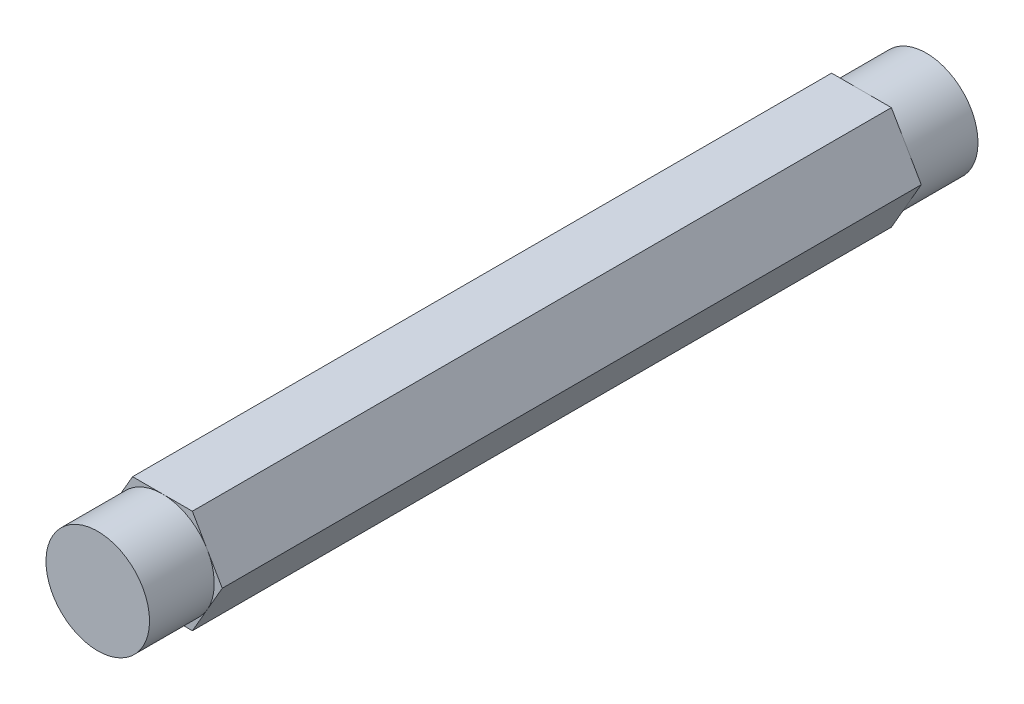
SolidWorks part; units mm, degrees
material "6061-T6 (SS)"
ref_plane "Front Plane" through (0, 0, 0) normal (0, 0, 1) x (1, 0, 0)
ref_plane "Top Plane" through (0, 0, 0) normal (0, 1, 0) x (1, 0, 0)
ref_plane "Right Plane" through (0, 0, 0) normal (1, 0, 0) x (0, 0, -1)
sketch "Sketch1" plane through (0, 0, 0) normal (0, 0, 1) x (1, 0, 0)
  line L1 (7.3323, 0) -> (3.6662, 6.35)
  line L2 (3.6662, 6.35) -> (-3.6662, 6.35)
  line L3 (-3.6662, 6.35) -> (-7.3323, 0)
  line L4 (-7.3323, 0) -> (-3.6662, -6.35)
  line L5 (-3.6662, -6.35) -> (3.6662, -6.35)
  line L6 (3.6662, -6.35) -> (7.3323, 0)
  circle A0 centre (0, 0) radius 6.35 construction
  circle A1 centre (0, 0) radius 6.875 construction
  circle A2 centre (0, 0) radius 2 construction
  dimension "D1" = 12.7
  dimension "D2" = 13.75
  dimension "D3" = 4
extrude "Boss-Extrude1" add sketch "Sketch1" along normal mid plane 101.6 contours L1 A1 L2 L3 L4 L5 L6
ref_plane "Plane1" through (0, 0, 42.8625) normal (0, 0, 1) x (1, 0, 0)
sketch "Sketch2" plane through (0, 0, 42.8625) normal (0, 0, 1) x (1, 0, 0)
  circle A0 centre (0, 0) radius 6.35
  point P3 (0, 0)
  point P4 (0, 0)
  dimension "D1" = 12.7
extrude "Cut-Extrude-Thin1" cut sketch "Sketch2" along normal up to next thin
mirror "Mirror1" about plane through (0, 0, 0) normal (0, 0, 1) of "Cut-Extrude-Thin1"
equation "\"D2@Sketch1\"=13.75mm"
equation "\"D3@Sketch1\"=4mm"
